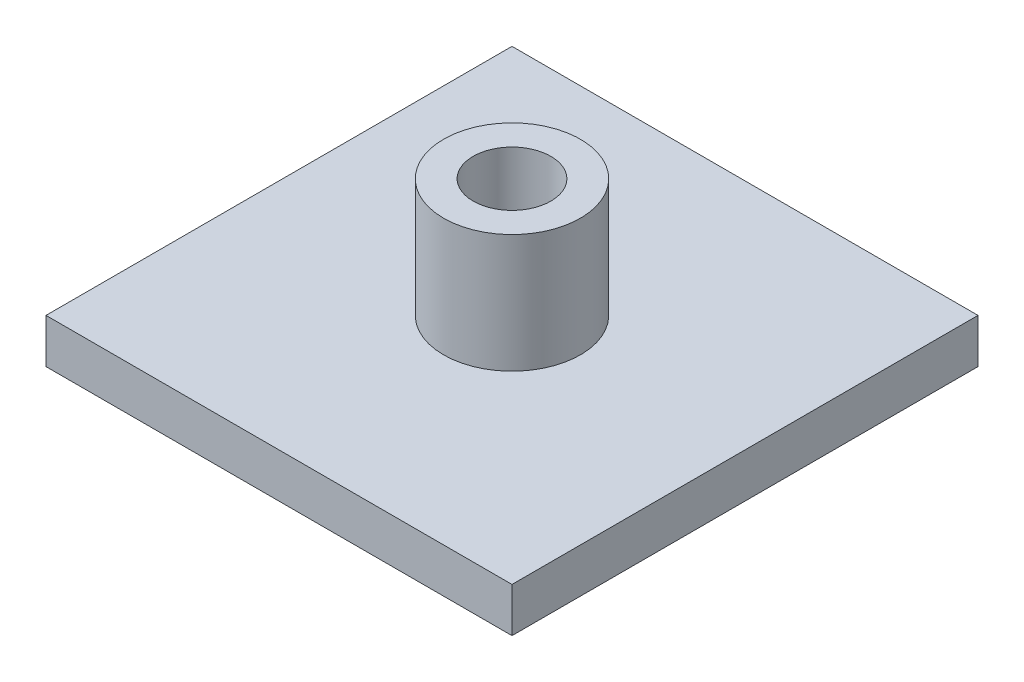
SolidWorks part; units mm, degrees
ref_plane "Front Plane" through (0, 0, 0) normal (0, 0, 1) x (1, 0, 0)
ref_plane "Top Plane" through (0, 0, 0) normal (0, 1, 0) x (1, 0, 0)
ref_plane "Right Plane" through (0, 0, 0) normal (1, 0, 0) x (0, 0, -1)
sketch "Sketch1" plane through (0, 0, 0) normal (0, 1, 0) x (1, 0, 0)
  line L1 (0, 0) -> (31.5, 0)
  line L2 (0, 0) -> (0, 31.5)
  line L3 (0, 31.5) -> (31.5, 31.5)
  line L4 (31.5, 0) -> (31.5, 31.5)
  dimension "D1" = 31.5
  dimension "D2" = 31.5
extrude "Boss-Extrude1" add sketch "Sketch1" along normal blind 3
sketch "Sketch2" plane through (0, 3, 0) normal (0, 1, 0) x (1, 0, 0)
  circle A0 centre (15.75, 15.75) radius 2.625
  circle A1 centre (15.75, 15.75) radius 4.625
  dimension "D1" = 5.25
  dimension "D2" = 2
extrude "Boss-Extrude2" add sketch "Sketch2" along normal blind 8
